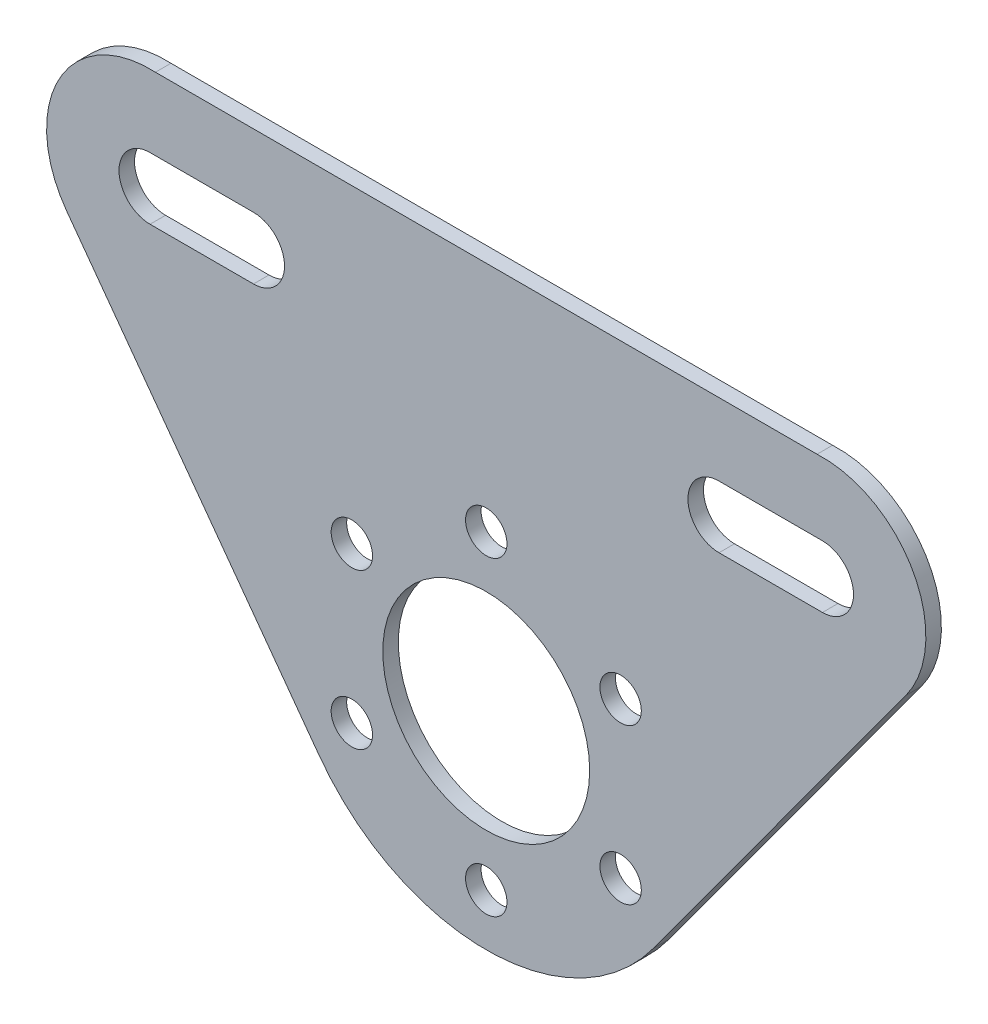
SolidWorks part; units mm, degrees
ref_plane "Front Plane" through (0, 0, 0) normal (0, 0, 1) x (1, 0, 0)
ref_plane "Top Plane" through (0, 0, 0) normal (0, 1, 0) x (1, 0, 0)
ref_plane "Right Plane" through (0, 0, 0) normal (1, 0, 0) x (0, 0, -1)
sketch "Sketch1" plane through (0, 0, 0) normal (0, 0, 1) x (1, 0, 0)
  line L3 (-32.2872, 16.3878) -> (-81.1436, 83.1939)
  line L8 (0, 0) -> (0, 140) construction
  line L9 (-65, 95) -> (-45, 95) construction
  line L10 (-65, 101) -> (-45, 101)
  line L11 (-65, 89) -> (-45, 89)
  line L12 (-63.9565, 114.9728) -> (63.9565, 114.9728)
  line L13 (65, 95) -> (45, 95) construction
  line L14 (65, 101) -> (45, 101)
  line L15 (65, 89) -> (45, 89)
  line L16 (32.2872, 16.3878) -> (81.1436, 83.1939)
  circle A4 centre (0, 40) radius 20
  circle A5 centre (0, 70) radius 4
  arc A6 (-65, 101) -> (-65, 89) centre (-65, 95) ccw
  arc A7 (-45, 89) -> (-45, 101) centre (-45, 95) ccw
  circle A8 centre (0, 40) radius 30 construction
  arc A9 (-32.2872, 16.3878) -> (32.2872, 16.3878) centre (0, 40) ccw
  arc A11 (-81.1436, 83.1939) -> (-63.9565, 114.9728) centre (-65, 95) cw
  arc A12 (65, 101) -> (65, 89) centre (65, 95) cw
  arc A13 (45, 89) -> (45, 101) centre (45, 95) cw
  arc A14 (81.1436, 83.1939) -> (63.9565, 114.9728) centre (65, 95) ccw
  circle A15 centre (25.9808, 55) radius 4
  circle A16 centre (25.9808, 25) radius 4
  circle A17 centre (0, 10) radius 4
  circle A18 centre (-25.9808, 25) radius 4
  circle A19 centre (-25.9808, 55) radius 4
  point P11 (-55, 95)
  point P21 (0, 0)
  point P22 (55, 95)
  point P32 (0, 114.9728)
  point P33 (32.2872, 30.7369)
  point P43 (0, 40)
  dimension "D4" = 40
  dimension "D5" = 8
  dimension "D6" = 60
  dimension "D8" = 40
  dimension "D9" = 20
  dimension "D1" = 20
  dimension "D2" = 12
  dimension "D3" = 45
  dimension "D7" = 55
  dimension "D10" = 127.9129
  dimension "D11" = 6
extrude "Boss-Extrude1" add sketch "Sketch1" along normal blind 3
